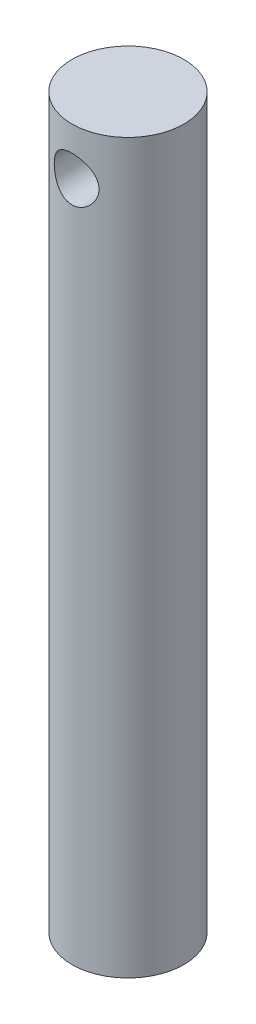
SolidWorks part; units mm, degrees
ref_plane "Front Plane" through (0, 0, 0) normal (0, 0, 1) x (1, 0, 0)
ref_plane "Top Plane" through (0, 0, 0) normal (0, 1, 0) x (1, 0, 0)
ref_plane "Right Plane" through (0, 0, 0) normal (1, 0, 0) x (0, 0, -1)
sketch "Эскиз1" plane through (0, 0, 0) normal (0, 1, 0) x (1, 0, 0)
  circle A0 centre (0, 0) radius 10
extrude "Вытянуть1" add sketch "Эскиз1" along normal blind 130
sketch "Эскиз2" plane through (0, 0, 0) normal (0, 0, 1) x (1, 0, 0)
  line L2 (10, 130) -> (-10, 130) construction
  circle A0 centre (0, 121.5) radius 4
  dimension "D1" = 8.5
extrude "Вытянуть2" cut sketch "Эскиз2" against normal mid plane 50
